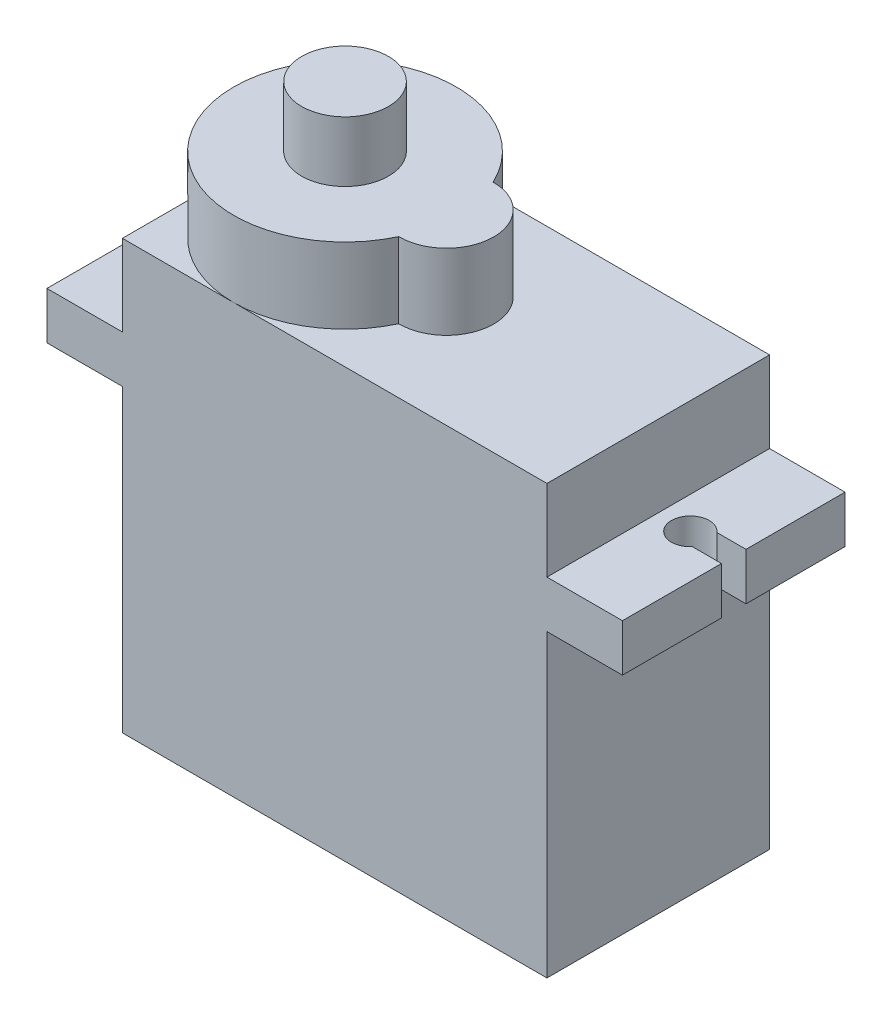
SolidWorks part; units mm, degrees
ref_plane "Front Plane" through (0, 0, 0) normal (0, 0, 1) x (1, 0, 0)
ref_plane "Top Plane" through (0, 0, 0) normal (0, 1, 0) x (1, 0, 0)
ref_plane "Right Plane" through (0, 0, 0) normal (1, 0, 0) x (0, 0, -1)
sketch "Sketch2" plane through (0, 0, 0) normal (0, 0, 1) x (1, 0, 0)
  line L1 (-5.9327, 14.8686) -> (16.5673, 14.8686)
  line L2 (-5.9327, 14.8686) -> (-5.9327, -7.8314)
  line L3 (-5.9327, -7.8314) -> (16.5673, -7.8314)
  line L4 (16.5673, 14.8686) -> (16.5673, -7.8314)
extrude "Boss-Extrude1" add sketch "Sketch2" along normal blind 11.8
sketch "Sketch3" plane through (0, 14.8686, 0) normal (0, 1, 0) x (1, 0, 0)
  circle A1 centre (-0.0327, -5.9) radius 5.9
  arc A3 (5.3116, -3.4002) -> (5.3116, -8.3998) centre (5.3441, -5.9) cw
extrude "Boss-Extrude2" add sketch "Sketch3" along normal blind 4 contours A1 | A3 A1
sketch "Sketch4" plane through (0, 18.8686, 0) normal (0, 1, 0) x (1, 0, 0)
  line L0 (-0.0327, 0) -> (-0.0327, -11.8)
  arc A0 (5.3116, -3.4002) -> (5.3116, -8.3998) centre (-0.0327, -5.9) ccw construction
  circle A1 centre (-0.0327, -5.9) radius 2.3
extrude "Boss-Extrude3" add sketch "Sketch4" along normal blind 3.2 contours A1
sketch "Sketch5" plane through (16.5673, 0, 0) normal (1, 0, 0) x (0, 0, -1)
  line L0 (0, -7.8314) -> (0, 14.8686) construction
  line L2 (-11.8, 10.5686) -> (-11.8, 8.0686)
  line L3 (-11.8, 10.5686) -> (0, 10.5686)
  line L4 (-11.8, 8.0686) -> (0, 8.0686)
  line L5 (0, 10.5686) -> (0, 8.0686)
  line L6 (-11.8, 10.5686) -> (0, 8.0686) construction
  line L7 (-11.8, 8.0686) -> (0, 10.5686) construction
  point P5 (-5.9, 9.3186)
extrude "Boss-Extrude4" add sketch "Sketch5" along normal blind 4 and the other way blind 26.5
sketch "Sketch7" plane through (0, 10.5686, 0) normal (0, 1, 0) x (1, 0, 0)
  line L0 (20.5673, -5.25) -> (20.5673, -6.55)
  line L1 (20.5673, 0) -> (20.5673, -11.8) construction
  line L2 (-9.9327, -4.9) -> (-9.9327, -6.2)
  line L3 (19.0272, -5.25) -> (20.5673, -5.25)
  line L4 (19.0272, -6.55) -> (20.5673, -6.55)
  line L6 (-8.3926, -4.9) -> (-9.9327, -4.9)
  line L7 (-8.3926, -6.2) -> (-9.9327, -6.2)
  arc A3 (-8.3926, -4.9) -> (-8.3926, -6.2) centre (-7.6327, -5.55) cw
  arc A4 (19.0272, -5.25) -> (19.0272, -6.55) centre (18.2673, -5.9) ccw
  point P8 (18.2673, -5.9)
  point P24 (-7.6327, -5.55)
  line M3 (20.5673, -11.8) -> (20.5673, 0)
extrude "Cut-Extrude1" cut sketch "Sketch7" against normal up to next contours L3 A4 L4 M3 | A3 L7 L2 L6
